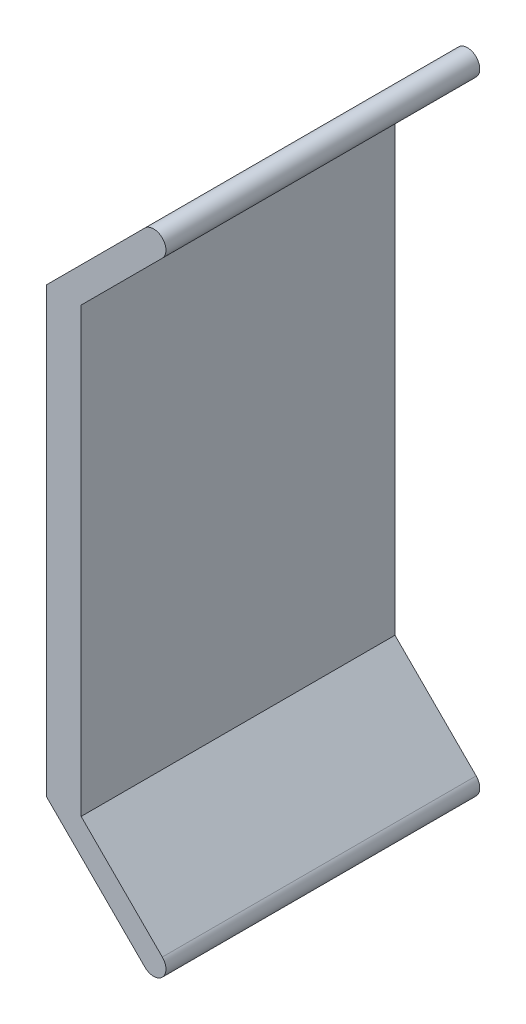
SolidWorks part; units mm, degrees
ref_plane "Alzado" through (0, 0, 0) normal (0, 0, 1) x (1, 0, 0)
ref_plane "Planta" through (0, 0, 0) normal (0, 1, 0) x (1, 0, 0)
ref_plane "Vista lateral" through (0, 0, 0) normal (1, 0, 0) x (0, 0, -1)
sketch "Croquis1" plane through (0, 0, 0) normal (0, 0, 1) x (1, 0, 0)
  line L0 (-5, 31.75) -> (-5, -31.75)
  line L1 (-5, -31.75) -> (9.1421, -45.8921)
  line L2 (11.6421, -43.3921) -> (0, -31.75)
  line L3 (0, -31.75) -> (0, 31.75)
  line L4 (0, 31.75) -> (11.6421, 43.3921)
  line L5 (9.1421, 45.8921) -> (-5, 31.75)
  arc A0 (9.1421, -45.8921) -> (11.6421, -43.3921) centre (10.3921, -44.6421) ccw
  arc A1 (11.6421, 43.3921) -> (9.1421, 45.8921) centre (10.3921, 44.6421) ccw
  point P10 (0, 0)
extrude "Saliente-Extruir1" add sketch "Croquis1" along normal blind 50
sketch "Croquis4" plane through (0, 0, 0) normal (0, 0, -1) x (-1, 0, 0)
  line L6 (5, 31.75) -> (-9.1421, 45.8921)
  line L7 (-11.6421, 43.3921) -> (0, 31.75)
  line L8 (0, 31.75) -> (0, -31.75)
  line L9 (0, -31.75) -> (-11.6421, -43.3921)
  line L10 (-9.1421, -45.8921) -> (5, -31.75)
  line L11 (5, -31.75) -> (5, 31.75)
  line L12 (5, 31.75) -> (-9.1421, 45.8921)
  line L13 (-11.6421, 43.3921) -> (0, 31.75)
  line L14 (0, 31.75) -> (0, -31.75)
  line L15 (0, -31.75) -> (-11.6421, -43.3921)
  line L16 (-9.1421, -45.8921) -> (5, -31.75)
  line L17 (5, -31.75) -> (5, 31.75)
  arc A2 (-9.1421, 45.8921) -> (-11.6421, 43.3921) centre (-10.3921, 44.6421) ccw
  arc A3 (-11.6421, -43.3921) -> (-9.1421, -45.8921) centre (-10.3921, -44.6421) ccw
  arc A4 (-9.1421, 45.8921) -> (-11.6421, 43.3921) centre (-10.3921, 44.6421) ccw
  arc A5 (-11.6421, -43.3921) -> (-9.1421, -45.8921) centre (-10.3921, -44.6421) ccw
  dimension "D1" = 0
extrude "Cortar-Extruir3" cut sketch "Croquis4" against normal blind 5
